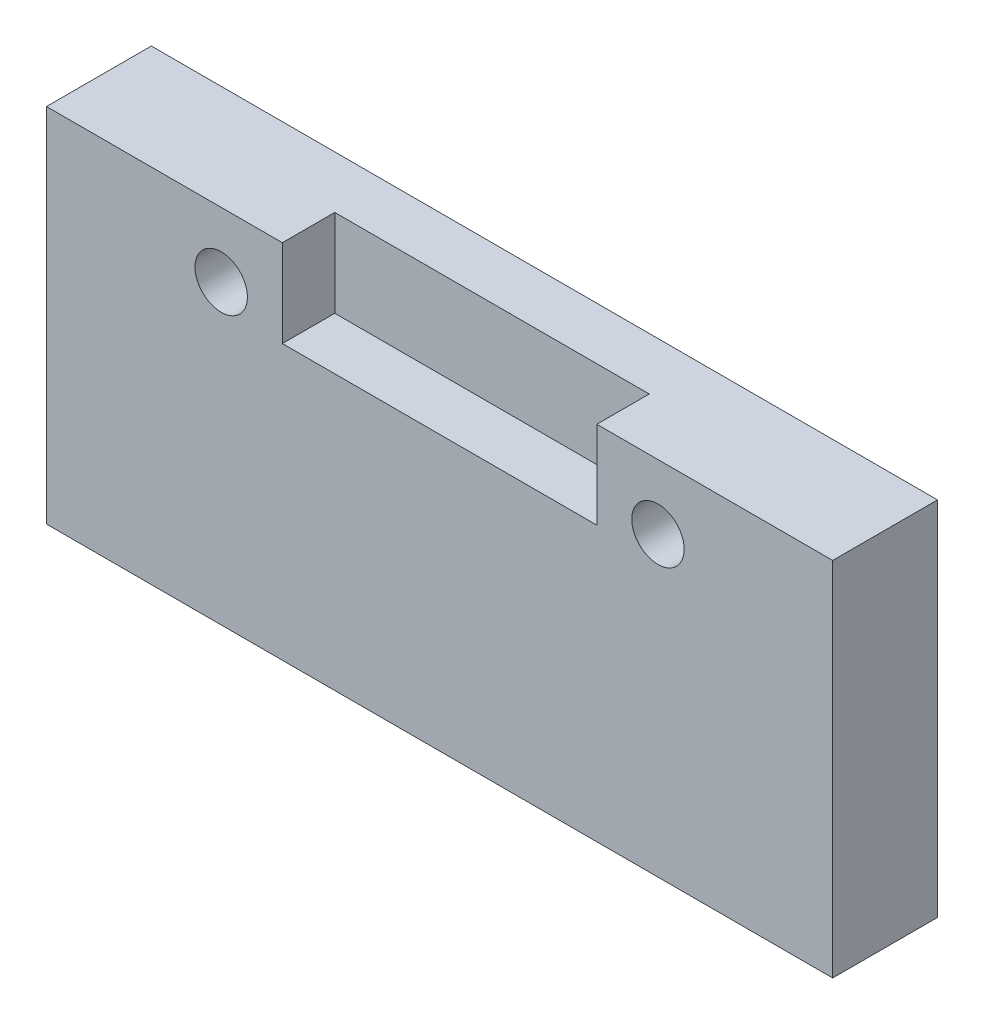
SolidWorks part; units mm, degrees
ref_plane "Front Plane" through (0, 0, 0) normal (0, 0, 1) x (1, 0, 0)
ref_plane "Top Plane" through (0, 0, 0) normal (0, 1, 0) x (1, 0, 0)
ref_plane "Right Plane" through (0, 0, 0) normal (1, 0, 0) x (0, 0, -1)
sketch "Sketch1" plane through (0, 0, 0) normal (0, 0, 1) x (1, 0, 0)
  line L0 (-18.4534, 12.206) -> (-18.4534, -8.494)
  line L1 (-18.4534, -8.494) -> (26.5466, -8.494)
  line L2 (26.5466, -8.494) -> (26.5466, 12.206)
  line L3 (26.5466, 12.206) -> (-18.4534, 12.206)
  line L4 (-18.4534, -4.494) -> (26.5466, -4.494) construction
  line L5 (-4.9534, 12.206) -> (-4.9534, 7.206) construction
  line L6 (-4.9534, 7.206) -> (13.0466, 7.206) construction
  line L7 (13.0466, 7.206) -> (13.0466, 12.206) construction
  circle A0 centre (16.5466, 8.506) radius 1.5
  circle A1 centre (-8.4534, 8.506) radius 1.5
  dimension "D3" = 3
  dimension "D4" = 3
  dimension "D8" = 3.7
  dimension "D9" = 13
  dimension "D10" = 22
  dimension "D7" = 3.7
  dimension "D11" = 20.7
  dimension "D13" = 2
  dimension "D2" = 4
  dimension "D12" = 2
  dimension "D1" = 45
  dimension "D5" = 10
  dimension "D6" = 10
  dimension "D14" = 5
  dimension "D15" = 11.7
extrude "Boss-Extrude1" add sketch "Sketch1" along normal blind 6
sketch "Sketch3" plane through (0, 0, 6) normal (0, 0, 1) x (1, 0, 0)
  line L0 (-4.9534, 12.206) -> (-4.9534, 7.206)
  line L1 (26.5466, 12.206) -> (-18.4534, 12.206) construction
  line L2 (-4.9534, 7.206) -> (13.0466, 7.206)
  line L3 (13.0466, 7.206) -> (13.0466, 12.206)
  line L4 (13.0466, 12.206) -> (-4.9534, 12.206)
  line L5 (-18.4534, -8.494) -> (26.5466, -8.494) construction
  circle A0 centre (-8.4534, 8.506) radius 1.5 construction
  circle A2 centre (16.5466, 8.506) radius 1.5 construction
  dimension "D1" = 2
  dimension "D2" = 2
  dimension "D3" = 5
  dimension "D4" = 15.7
extrude "Cut-Extrude1" cut sketch "Sketch3" against normal blind 3
